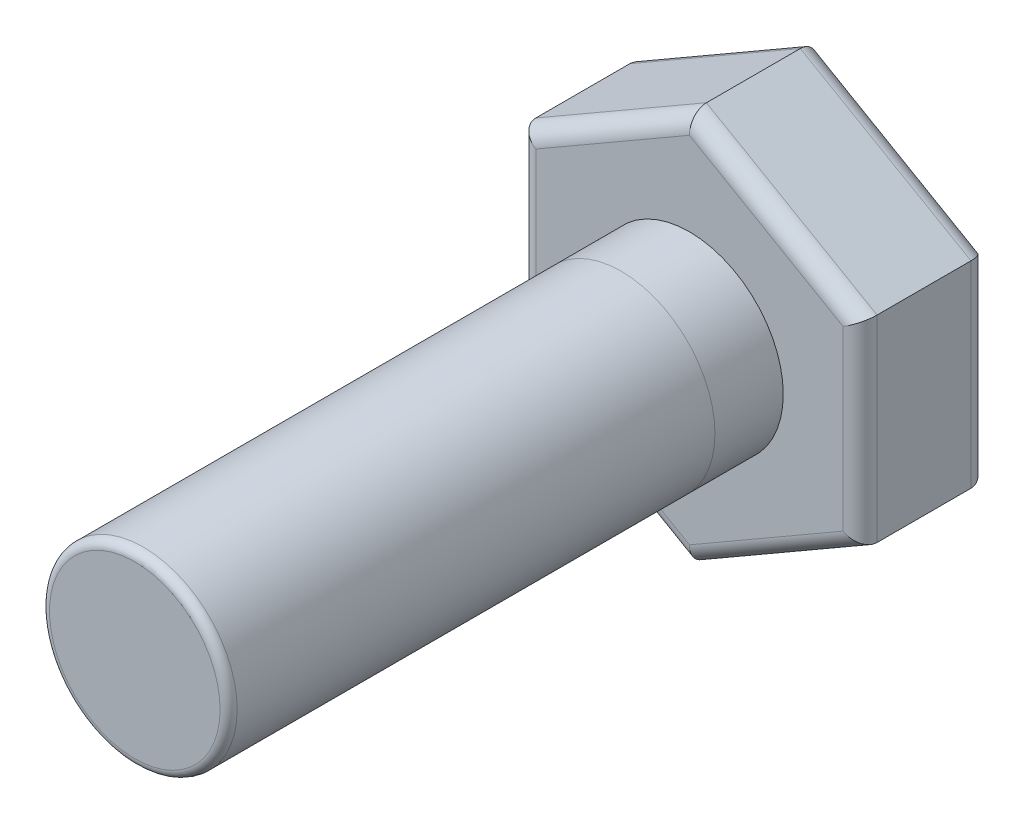
SolidWorks part; units mm, degrees
ref_plane "前视" through (0, 0, 0) normal (0, 0, 1) x (1, 0, 0)
ref_plane "上视" through (0, 0, 0) normal (0, 1, 0) x (1, 0, 0)
ref_plane "右视" through (0, 0, 0) normal (1, 0, 0) x (0, 0, -1)
sketch "草图1" plane through (0, 0, 0) normal (0, 0, 1) x (1, 0, 0)
  line L1 (20, 11.547) -> (0, 23.094)
  line L2 (0, 23.094) -> (-20, 11.547)
  line L3 (-20, 11.547) -> (-20, -11.547)
  line L4 (-20, -11.547) -> (0, -23.094)
  line L5 (0, -23.094) -> (20, -11.547)
  line L6 (20, -11.547) -> (20, 11.547)
  circle A0 centre (0, 0) radius 20 construction
  dimension "D1" = 40
extrude "基体-拉伸" add sketch "草图1" along normal blind 15
sketch "草图2" plane through (0, 0, 15) normal (0, 0, 1) x (1, 0, 0)
  circle A0 centre (0, 0) radius 11
  dimension "D1" = 22
extrude "凸台-拉伸1" add sketch "草图2" along normal blind 8
fillet "圆角3" radius 2 12 edges at (-10, 17.3205, 15) (-20, 0, 15) (-10, -17.3205, 15) (10, -17.3205, 15) (20, 0, 15) (10, -17.3205, 0) (-10, -17.3205, 0) (-20, 0, 0) (10, 17.3205, 15) (-10, 17.3205, 0) (10, 17.3205, 0) (20, 0, 0)
sketch "草图3" plane through (0, 0, 23) normal (0, 0, 1) x (1, 0, 0)
  circle A0 centre (0, 0) radius 10.995
  dimension "D1" = 21.99
extrude "拉伸1" add sketch "草图3" along normal blind 57
fillet "圆角4" radius 1 1 edges at (10.995, 0, 80)
